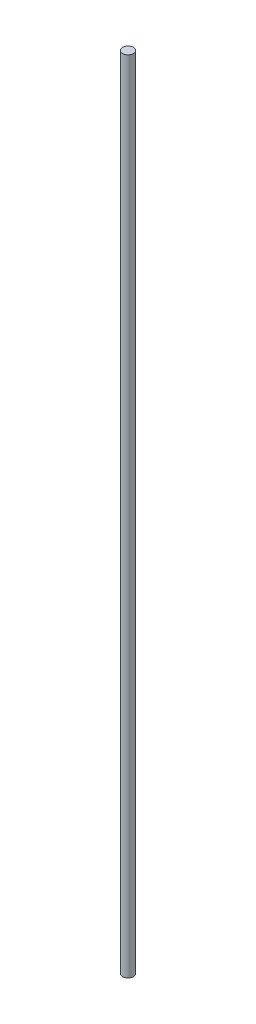
SolidWorks part; units mm, degrees
ref_plane "Front Plane" through (0, 0, 0) normal (0, 0, 1) x (1, 0, 0)
ref_plane "Top Plane" through (0, 0, 0) normal (0, 1, 0) x (1, 0, 0)
ref_plane "Right Plane" through (0, 0, 0) normal (1, 0, 0) x (0, 0, -1)
sketch "Sketch1" plane through (0, 0, 0) normal (0, 1, 0) x (1, 0, 0)
  circle A0 centre (0, 0) radius 2.921
  dimension "D1" = 5.842
extrude "Boss-Extrude1" add sketch "Sketch1" along normal blind 431.8
